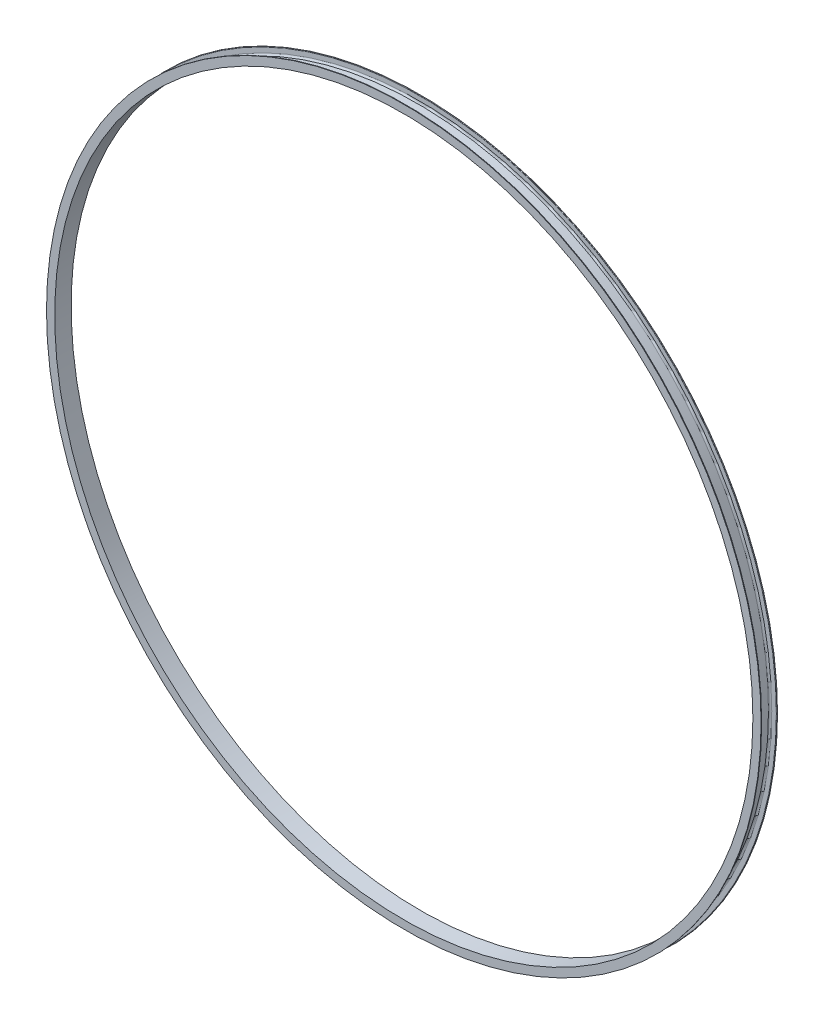
SolidWorks part; units mm, degrees
material "ASTM A36 Steel"
ref_plane "Front Plane" through (0, 0, 0) normal (0, 0, 1) x (1, 0, 0)
ref_plane "Top Plane" through (0, 0, 0) normal (0, 1, 0) x (1, 0, 0)
ref_plane "Right Plane" through (0, 0, 0) normal (1, 0, 0) x (0, 0, -1)
sketch "Sketch1" plane through (0, 0, 0) normal (0, 1, 0) x (1, 0, 0)
  line L1 (850, 0) -> (850, 20)
  line L2 (850, 0) -> (850, -20)
  line L3 (850, -20) -> (870, -20)
  line L4 (850, 20) -> (870, 20)
  line L5 (870, 20) -> (870, 19)
  line L6 (869, 18) -> (858, 18)
  line L7 (870, -20) -> (870, -19)
  line L8 (869, -18) -> (858, -18)
  line L9 (854, -14) -> (854, 14)
  line L10 (0, 0) -> (0, 136.1341) construction
  arc A0 (854, -14) -> (858, -18) centre (858, -14) ccw
  arc A1 (854, 14) -> (858, 18) centre (858, 14) cw
  arc A2 (869, -18) -> (870, -19) centre (869, -19) cw
  arc A3 (869, 18) -> (870, 19) centre (869, 19) ccw
  dimension "D1" = 4
  dimension "D2" = 1
revolve "Revolve1" add sketch "Sketch1" angle 360 about L10
